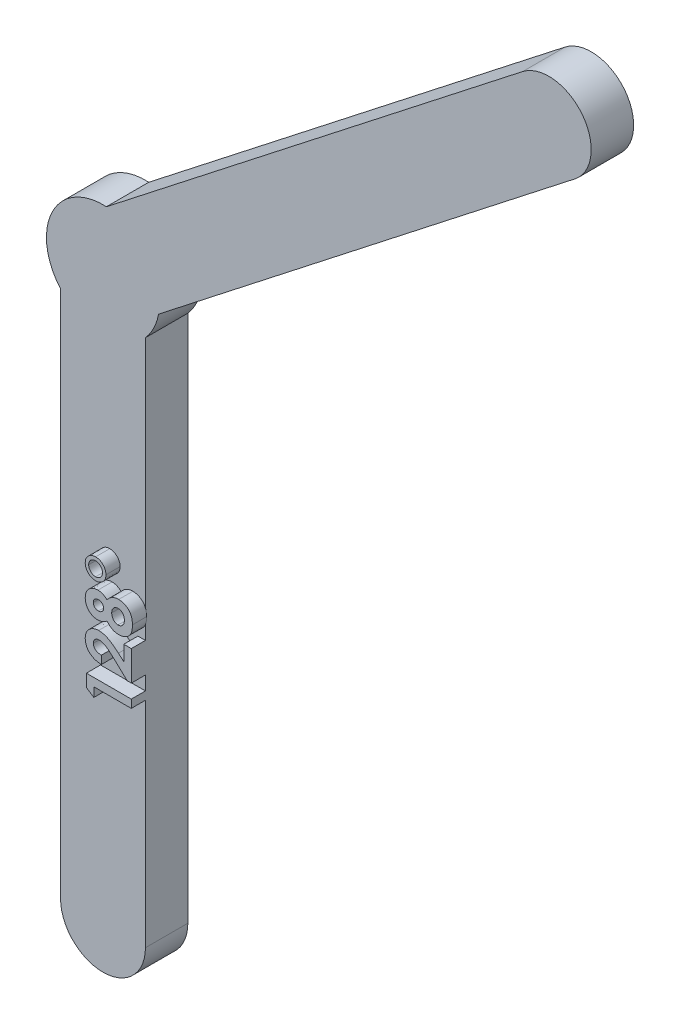
SolidWorks part; units mm, degrees
ref_plane "Front Plane" through (0, 0, 0) normal (0, 0, 1) x (1, 0, 0)
ref_plane "Top Plane" through (0, 0, 0) normal (0, 1, 0) x (1, 0, 0)
ref_plane "Right Plane" through (0, 0, 0) normal (1, 0, 0) x (0, 0, -1)
sketch "Sketch2" plane through (0, 0, 0) normal (0, 0, 1) x (1, 0, 0)
  line L0 (0, 0) -> (0, -40) construction
  line L1 (0, 0) -> (31.5204, 24.6265) construction
  line L2 (29.6734, 26.9905) -> (33.3674, 22.2624) construction
  line L3 (-3, -40) -> (3, -40) construction
  line L4 (-3, -40) -> (-3, -2.6458)
  line L5 (3, -40) -> (3, -2.6458)
  line L6 (29.6734, 26.9905) -> (0.2379, 3.9929)
  line L7 (33.3674, 22.2624) -> (3.9319, -0.7351)
  arc A0 (0.2379, 3.9929) -> (-3, -2.6458) centre (0, 0) ccw
  arc A1 (-3, -40) -> (3, -40) centre (0, -40) ccw
  arc A2 (29.6734, 26.9905) -> (33.3674, 22.2624) centre (31.5204, 24.6265) cw
  arc A3 (3, -2.6458) -> (3.9319, -0.7351) centre (0, 0) ccw
  point P12 (31.5204, 24.6265)
  dimension "D3" = 3
  dimension "D4" = 8
  dimension "D1" = 40
  dimension "D2" = 128
extrude "Boss-Extrude1" add sketch "Sketch2" along normal blind 3
sketch "Sketch3" plane through (0, 0, 3) normal (0, 0, 1) x (1, 0, 0)
  text T0 "<b>128°</b>"
extrude "Boss-Extrude2" add sketch "Sketch3" along normal blind 1
